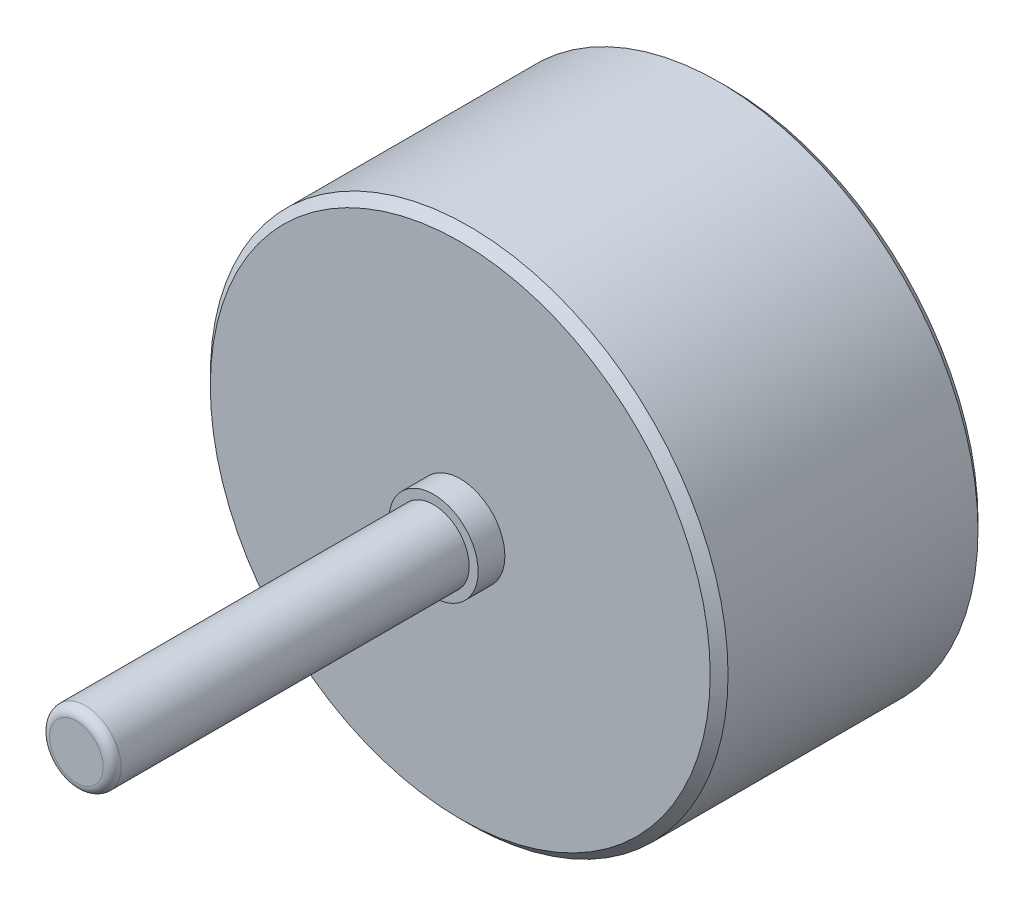
SolidWorks part; units mm, degrees
ref_plane "Plan de face" through (0, 0, 0) normal (0, 0, 1) x (1, 0, 0)
ref_plane "Plan de dessus" through (0, 0, 0) normal (0, 1, 0) x (1, 0, 0)
ref_plane "Plan de droite" through (0, 0, 0) normal (1, 0, 0) x (0, 0, -1)
sketch "Esquisse1" plane through (0, 0, 0) normal (0, 0, 1) x (1, 0, 0)
  circle A0 centre (0, 0) radius 29
extrude "Boss.-Extru.1" add sketch "Esquisse1" along normal blind 30
sketch "Esquisse2" plane through (0, 0, 30) normal (0, 0, 1) x (1, 0, 0)
  circle A0 centre (0, 0) radius 4
  dimension "D1" = 8
extrude "Boss.-Extru.2" add sketch "Esquisse2" along normal blind 10.25 contours A0
sketch "Esquisse3" plane through (0, 0, 30) normal (0, 0, 1) x (1, 0, 0)
  circle A0 centre (0, 0) radius 5
extrude "Boss.-Extru.3" add sketch "Esquisse3" along normal blind 3
sketch "Esquisse4" plane through (0, 0, 0) normal (0, 0, -1) x (-1, 0, 0)
  circle A0 centre (0, 0) radius 4
extrude "Enlèv. mat.-Extru.1" cut sketch "Esquisse4" against normal blind 5
chamfer "Chanfrein1" distance 1 angle 45 2 edges at (29, 0, 30) (29, 0, 0)
sketch "Esquisse5" plane through (0, 0, 40.25) normal (0, 0, 1) x (1, 0, 0)
  circle A0 centre (0, 0) radius 4
sketch "Esquisse8" plane through (0, 0, 40.25) normal (0, 0, 1) x (1, 0, 0)
  circle A0 centre (0, 0) radius 4
extrude "Boss.-Extru.4" add sketch "Esquisse8" along normal blind 32.75
fillet "Congé1" radius 1 1 edges at (4, 0, 73)
